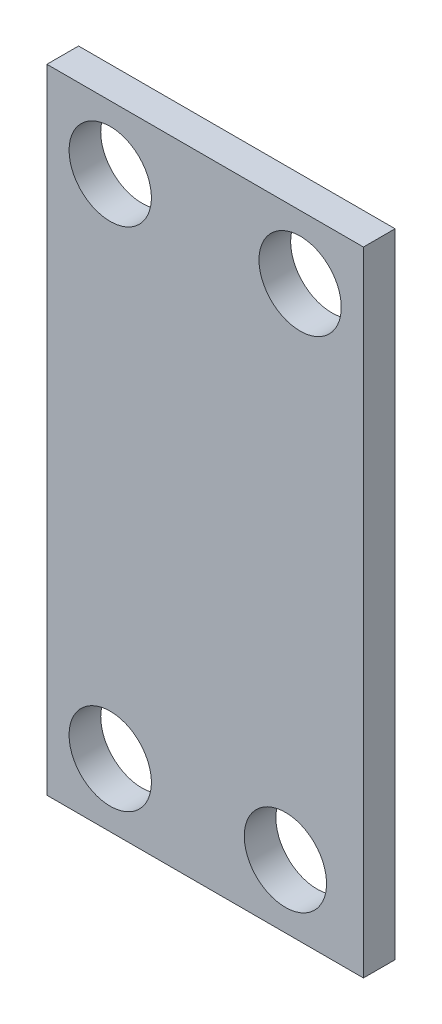
SolidWorks part; units mm, degrees
ref_plane "Front Plane" through (0, 0, 0) normal (0, 0, 1) x (1, 0, 0)
ref_plane "Top Plane" through (0, 0, 0) normal (0, 1, 0) x (1, 0, 0)
ref_plane "Right Plane" through (0, 0, 0) normal (1, 0, 0) x (0, 0, -1)
sketch "Sketch1" plane through (0, 0, 0) normal (0, 0, 1) x (1, 0, 0)
  line L1 (0, 0) -> (50, 0)
  line L2 (0, 0) -> (0, -100)
  line L3 (0, -100) -> (50, -100)
  line L4 (50, 0) -> (50, -100)
  dimension "D1" = 50
  dimension "D2" = 100
extrude "Boss-Extrude1" add sketch "Sketch1" along normal blind 5
sketch "Sketch2" plane through (0, 0, 0) normal (0, 0, -1) x (-1, 0, 0)
  line L0 (0, 0) -> (0, -100) construction
  line L1 (-50, -100) -> (-50, 0) construction
  line L2 (0, -100) -> (-50, -100) construction
  line L3 (-50, 0) -> (0, 0) construction
  circle A0 centre (-10, -10) radius 6.5
  circle A1 centre (-40, -10) radius 6.5
  circle A2 centre (-10, -90) radius 6.5
  circle A3 centre (-37.6746, -90) radius 6.5
  dimension "D1" = 13
  dimension "D2" = 13
  dimension "D3" = 13
  dimension "D4" = 13
  dimension "D5" = 10
  dimension "D6" = 10
  dimension "D7" = 10
  dimension "D8" = 10
extrude "Cut-Extrude1" cut sketch "Sketch2" against normal through all
